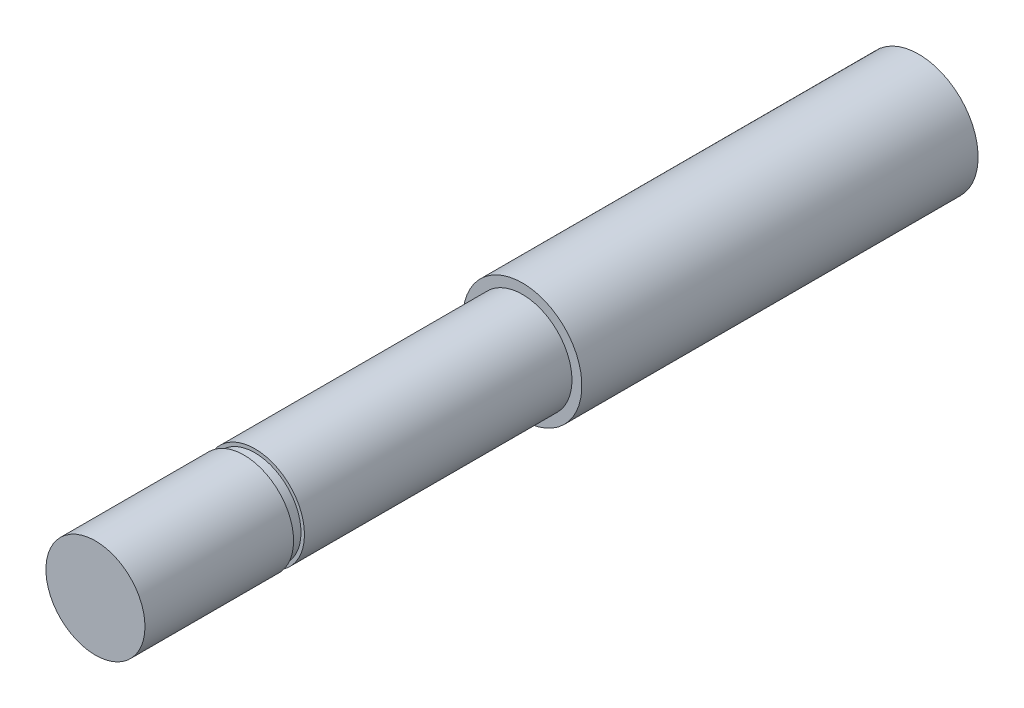
SolidWorks part; units mm, degrees
material "SKD11淬火HRC56-60"
ref_plane "前基準面" through (0, 0, 0) normal (0, 0, 1) x (1, 0, 0)
ref_plane "上基準面" through (0, 0, 0) normal (0, 1, 0) x (1, 0, 0)
ref_plane "右基準面" through (0, 0, 0) normal (1, 0, 0) x (0, 0, -1)
sketch "草图1" plane through (0, 0, 0) normal (0, 0, 1) x (1, 0, 0)
  circle A0 centre (0, 0) radius 5
  dimension "D1" = 10
extrude "凸台-拉伸1" add sketch "草图1" along normal blind 27
sketch "草图2" plane through (0, 0, 0) normal (0, 0, -1) x (-1, 0, 0)
  circle A0 centre (0, 0) radius 6
  dimension "D1" = 12
extrude "凸台-拉伸2" add sketch "草图2" along normal blind 40
sketch "草图3" plane through (0, 0, 27) normal (0, 0, 1) x (1, 0, 0)
  circle A0 centre (0, 0) radius 4.65
  dimension "D1" = 9.3
extrude "凸台-拉伸3" add sketch "草图3" along normal blind 1.1
sketch "草图4" plane through (0, 0, 28.1) normal (0, 0, 1) x (1, 0, 0)
  circle A1 centre (0, 0) radius 5
  circle A2 centre (0, 0) radius 5
  dimension "D1" = 0
extrude "凸台-拉伸4" add sketch "草图4" along normal blind 15
